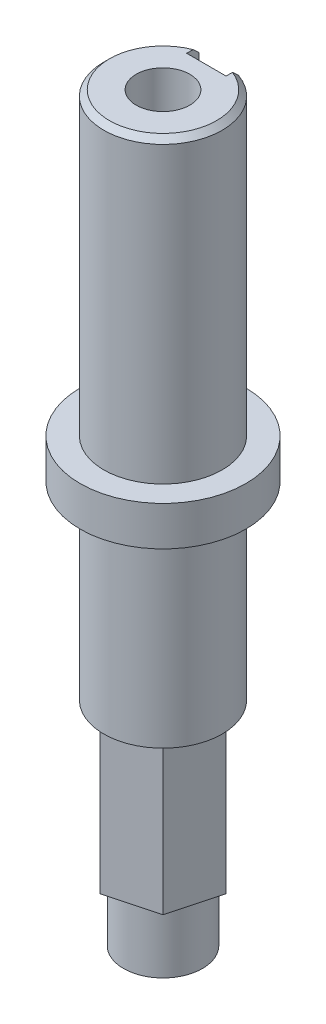
SolidWorks part; units mm, degrees
material "AISI 4340 Aço, normalizado"
ref_plane "Plano frontal" through (0, 0, 0) normal (0, 0, 1) x (1, 0, 0)
ref_plane "Plano superior" through (0, 0, 0) normal (0, 1, 0) x (1, 0, 0)
ref_plane "Plano direito" through (0, 0, 0) normal (1, 0, 0) x (0, 0, -1)
sketch "Esboço1" plane through (0, 0, 0) normal (0, 0, 1) x (1, 0, 0)
  line L0 (0, -47) -> (0, -62.1088) construction
  line L1 (6.7929, 47) -> (4, 47)
  line L2 (6.7929, 47) -> (7.5, 46.2929)
  line L3 (7.5, 46.2929) -> (7.5, -11)
  line L9 (7.5, -39) -> (5, -39)
  line L10 (5, -39) -> (5, -47)
  line L11 (5, -47) -> (0, -47)
  line L17 (0, -47) -> (0, 23)
  line L19 (7.5, -11) -> (7.5, -39)
  line L20 (0, 23) -> (0, 47)
  line L21 (0, 47) -> (4, 47)
  dimension "D1" = 94
  dimension "D2" = 47
  dimension "D4" = 5
  dimension "D5" = 8
  dimension "D6" = 7.5
  dimension "D8" = 28
  dimension "D12" = 4
  dimension "D13" = 45
  dimension "D14" = 1
revolve "Revolução1" add sketch "Esboço1" angle 360 about L0
sketch "Esboço2" plane through (0, 47, 0) normal (0, 1, 0) x (1, 0, 0)
  line L1 (-2.5, 5.5) -> (2.5, 5.5)
  line L3 (-2.5, 5.5) -> (-2.5, 11.5)
  line L4 (-2.5, 11.5) -> (2.5, 11.5)
  line L5 (2.5, 11.5) -> (2.5, 5.5)
  circle A1 centre (0, 0) radius 7.5 construction
  dimension "D1" = 2.5
  dimension "D2" = 5
  dimension "D3" = 6
  dimension "D4" = 5.5
extrude "Corte-extrusão1" cut sketch "Esboço2" against normal blind 22
ref_plane "Plano1" through (0, 25, -7.5) normal (0, 0, -1) x (-1, 0, 0)
sketch "Esboço3" plane through (0, 25, -7.5) normal (0, 0, -1) x (-1, 0, 0)
  line L0 (2.5, 0) -> (-2.5, 0)
  line L2 (2.5, 0) -> (-2.5, 0) construction
  line L3 (2.5, 0) -> (-2.5, 0) construction
  arc A0 (2.5, 0) -> (-2.5, 0) centre (0, 0) cw
  dimension "D1" = 2.5
extrude "Corte-extrusão2" cut sketch "Esboço3" against normal up to surface (2 mm away) up to face at (0, 36, -5.5)
sketch "Esboço5" plane through (0, -39, 0) normal (0, -1, 0) x (1, 0, 0)
  line L6 (-4.5962, -4.5962) -> (0, 0) construction
  line L7 (-4.5962, -4.5962) -> (1.6823, -6.2785)
  line L8 (1.6823, -6.2785) -> (6.2785, -1.6823)
  line L9 (6.2785, -1.6823) -> (4.5962, 4.5962)
  line L10 (4.5962, 4.5962) -> (-1.6823, 6.2785)
  line L11 (-1.6823, 6.2785) -> (-6.2785, 1.6823)
  line L12 (-6.2785, 1.6823) -> (-4.5962, -4.5962)
  line L13 (0, 0) -> (-7.5, 0) construction
  circle A0 centre (0, 0) radius 7.5 construction
  circle A3 centre (0, 0) radius 5.6292 construction
  circle A5 centre (0, 0) radius 12.651
  dimension "D1" = 45
  dimension "D3" = 13
extrude "Corte-extrusão8" cut sketch "Esboço5" against normal blind 19
hole_wizard "Broca de rosquear para tarraxa de M5x0.81" positions "Esboço8" profile "Esboço7" hole size "M5x0.8" standard "Ansi Metric"
sketch "Esboço8" plane through (0, -47, 0) normal (0, -1, 0) x (-1, 0, 0)
  point P0 (0, 0)
sketch "Esboço7" plane through (0, -47, 0) normal (1, 0, 0) x (0, 0, -1)
  line L0 (0, 0) -> (0, 11.2618)
  line L1 (0, 11.2618) -> (2.1, 10)
  line L2 (2.1, 10) -> (2.1, 0)
  line L5 (2.1, 0) -> (0, 0)
  line L10 (0, 11.2618) -> (-2.1, 10) construction
  line L11 (0, -6.35) -> (0, 107.95) construction
  dimension "Hole Dia." = 4.2
  dimension "Hole Depth" = 10
  dimension "Drill Angle" = 118
chamfer "Chanfro1" distance 0.5 angle 45 1 edges at (0, -47, -2.1)
ref_plane "Plano2" through (0, 0, 0) normal (-0.2588, 0, -0.9659) x (-0.9659, 0, 0.2588)
sketch "Esboço10" plane through (0, 0, 0) normal (-0.2588, 0, -0.9659) x (-0.9659, 0, 0.2588)
  line L0 (7.5, 9) -> (7.5, 4)
  line L1 (7.5, -20) -> (7.5, 46.2929) construction
  line L2 (7.5, 4) -> (10.5, 4)
  line L3 (10.5, 4) -> (10.5, 9)
  line L4 (10.5, 9) -> (7.5, 9)
  line L5 (6.7929, 47) -> (-6.7929, 47) construction
  dimension "D1" = 5
  dimension "D2" = 38
  dimension "D3" = 3
ref_axis "Eixo1" through (0, -20, 0) along (0, 1, 0)
revolve "Revolução2" add sketch "Esboço10" angle 360 about axis through (0, -20, 0) along (0, 1, 0)
hole_wizard "Broca de rosquear para tarraxa de M81" positions "Esboço11" profile "Esboço12" hole size "M8" standard "ISO"
sketch "Esboço11" plane through (0, 47, 0) normal (0, 1, 0) x (1, 0, 0)
  point P0 (0, 0)
sketch "Esboço12" plane through (0, 47, 0) normal (1, 0, 0) x (0, 0, 1)
  line L0 (0, 0) -> (0, 22.0429)
  line L1 (0, 22.0429) -> (3.4, 20)
  line L2 (3.4, 20) -> (3.4, 0)
  line L5 (3.4, 0) -> (0, 0)
  line L10 (0, 22.0429) -> (-3.4, 20) construction
  line L11 (0, -6.35) -> (0, 107.95) construction
  dimension "Hole Dia." = 6.8
  dimension "Hole Depth" = 20
  dimension "Drill Angle" = 118
